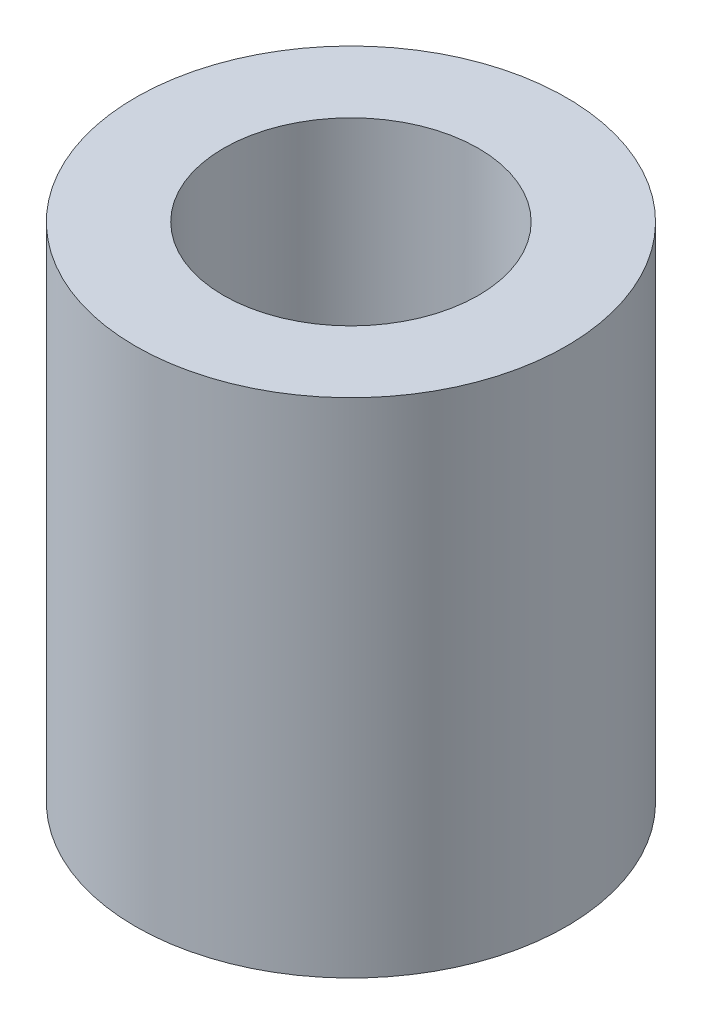
SolidWorks part; units mm, degrees
ref_plane "Front Plane" through (0, 0, 0) normal (0, 0, 1) x (1, 0, 0)
ref_plane "Top Plane" through (0, 0, 0) normal (0, 1, 0) x (1, 0, 0)
ref_plane "Right Plane" through (0, 0, 0) normal (1, 0, 0) x (0, 0, -1)
sketch "Sketch2" plane through (0, 0, 0) normal (0, 1, 0) x (1, 0, 0)
  circle A0 centre (0, 0) radius 3
  dimension "D1" = 6
extrude "Boss-Extrude1" add sketch "Sketch2" along normal blind 7
sketch "Sketch3" plane through (0, 7, 0) normal (0, 1, 0) x (1, 0, 0)
  circle A0 centre (0, 0) radius 1.775
  circle A1 centre (0, 0) radius 3 construction
  dimension "D1" = 3.55
extrude "Cut-Extrude1" cut sketch "Sketch3" against normal through all
